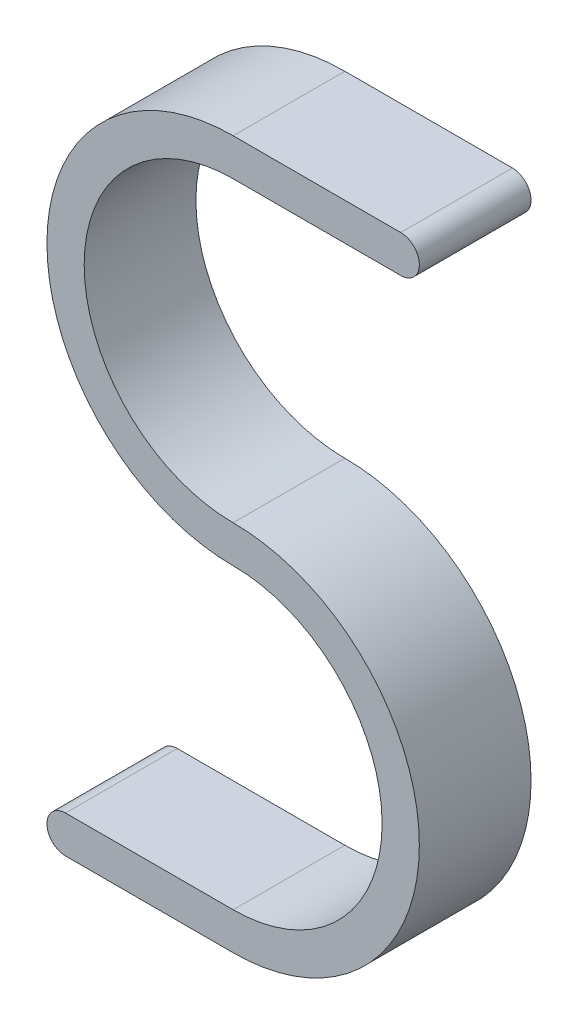
SolidWorks part; units mm, degrees
ref_plane "Ön Düzlem" through (0, 0, 0) normal (0, 0, 1) x (1, 0, 0)
ref_plane "Üst Düzlem" through (0, 0, 0) normal (0, 1, 0) x (1, 0, 0)
ref_plane "Sağ Düzlem" through (0, 0, 0) normal (1, 0, 0) x (0, 0, -1)
sketch "Çizim3" plane through (0, 0, 0) normal (0, 0, 1) x (1, 0, 0)
  line L0 (0, 56.7513) -> (0, -59.5939) construction
  line L1 (0, 45) -> (22.5, 45)
  line L2 (22.5, 40) -> (0, 40)
  line L3 (0, -45) -> (-22.5, -45)
  line L4 (0, -50) -> (-22.5, -50)
  arc A0 (0, 40) -> (0, 0) centre (0, 20) ccw
  arc A1 (0, -50) -> (0, 0) centre (0, -25) ccw
  arc A2 (0, 45) -> (0, -5) centre (0, 20) ccw
  arc A3 (0, -45) -> (0, -5) centre (0, -25) ccw
  arc A4 (22.5, 45) -> (22.5, 40) centre (22.5, 42.5) cw
  arc A5 (-22.5, -50) -> (-22.5, -45) centre (-22.5, -47.5) cw
  dimension "D1" = 40
  dimension "D2" = 50
  dimension "D3" = 25
  dimension "D4" = 20
  dimension "D5" = 2.5
  dimension "D6" = 2.5
  dimension "D7" = 22.5
  dimension "D8" = 22.5
extrude "Yükseklik-Ekstrüzyon2" add sketch "Çizim3" along normal blind 15
